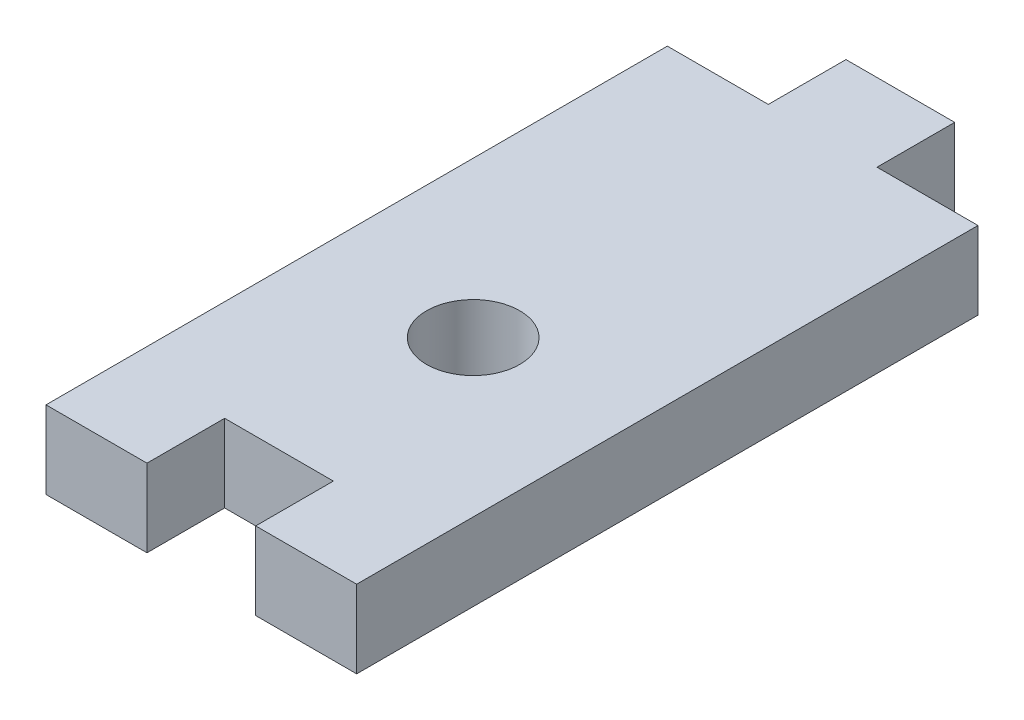
SolidWorks part; units mm, degrees
material "Acrylic (Medium-high impact)"
ref_plane "Front Plane" through (0, 0, 0) normal (0, 0, 1) x (1, 0, 0)
ref_plane "Top Plane" through (0, 0, 0) normal (0, 1, 0) x (1, 0, 0)
ref_plane "Right Plane" through (0, 0, 0) normal (1, 0, 0) x (0, 0, -1)
sketch "Sketch1" plane through (0, 0, 0) normal (0, 1, 0) x (1, 0, 0)
  line L0 (-10, 20) -> (-10, -20)
  line L1 (-10, -20) -> (-3.5, -20)
  line L2 (-3.5, -20) -> (-3.5, -15)
  line L3 (-3.5, -15) -> (3.5, -15)
  line L4 (3.5, -15) -> (3.5, -20)
  line L5 (3.5, -20) -> (10, -20)
  line L6 (10, -20) -> (10, 20)
  line L7 (10, 20) -> (3.5, 20)
  line L8 (3.5, 20) -> (3.5, 25)
  line L9 (3.5, 25) -> (-3.5, 25)
  line L10 (-3.5, 25) -> (-3.5, 20)
  line L11 (-3.5, 20) -> (-10, 20)
  point P11 (0, 25)
  point P13 (0, -15)
  point P15 (10, 0)
  dimension "D1" = 45
  dimension "D2" = 5
  dimension "D3" = 5
  dimension "D4" = 7
  dimension "D5" = 20
  dimension "D6" = 10
extrude "Boss-Extrude1" add sketch "Sketch1" along normal blind 5
sketch "Sketch2" plane through (0, 5, 0) normal (0, 1, 0) x (1, 0, 0)
  line L0 (-3.5, 20) -> (-10, 20) construction
  circle A0 centre (0, -2.5) radius 3
  dimension "D1" = 6
  dimension "D2" = 22.5
extrude "Cut-Extrude1" cut sketch "Sketch2" against normal blind 10
